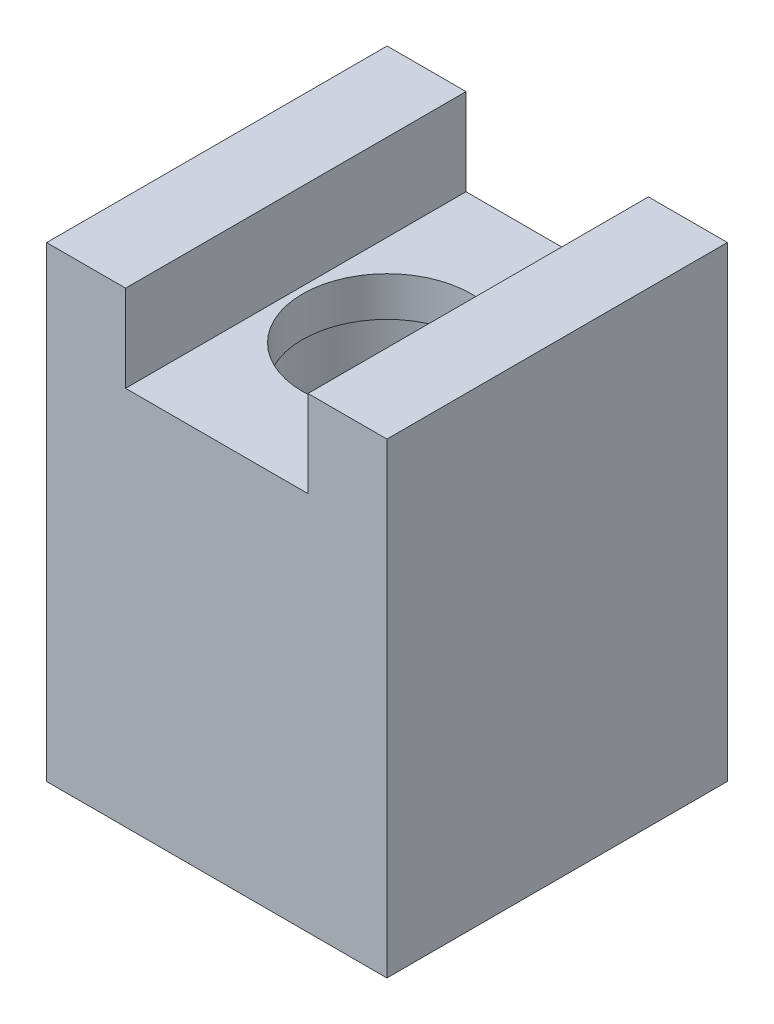
SolidWorks part; units mm, degrees
material "Alloy Steel (SS)"
ref_plane "Front Plane" through (0, 0, 0) normal (0, 0, 1) x (1, 0, 0)
ref_plane "Top Plane" through (0, 0, 0) normal (0, 1, 0) x (1, 0, 0)
ref_plane "Right Plane" through (0, 0, 0) normal (1, 0, 0) x (0, 0, -1)
sketch "Sketch1" plane through (0, 0, 0) normal (0, 1, 0) x (1, 0, 0)
  line L1 (-15.2171, -15.2248) -> (15.2171, -15.2248)
  line L2 (-15.2171, -15.2248) -> (-15.2171, 15.2248)
  line L3 (-15.2171, 15.2248) -> (15.2171, 15.2248)
  line L4 (15.2171, -15.2248) -> (15.2171, 15.2248)
  line L5 (-15.2171, -15.2248) -> (15.2171, 15.2248) construction
  line L6 (-15.2171, 15.2248) -> (15.2171, -15.2248) construction
  point P0 (0, 0)
  dimension "D1" = 30.4343
  dimension "D2" = 30.4495
extrude "Boss-Extrude1" add sketch "Sketch1" along normal blind 41.7424
sketch "Sketch4" plane through (0, 0, 0) normal (0, -1, 0) x (1, 0, 0)
  circle A0 centre (0, 0) radius 7.5565
  dimension "D1" = 15.113
extrude "Cut-Extrude3" cut sketch "Sketch4" against normal blind 36.5394
sketch "Sketch6" plane through (0, 41.7424, 0) normal (0, 1, 0) x (1, 0, 0)
  line L0 (15.2171, 15.2248) -> (-15.2171, 15.2248) construction
  line L1 (-8.1559, -15.2248) -> (8.1559, -15.2248)
  line L2 (-8.1559, -15.2248) -> (-8.1559, 15.2248)
  line L3 (-8.1559, 15.2248) -> (8.1559, 15.2248)
  line L4 (8.1559, -15.2248) -> (8.1559, 15.2248)
  line L5 (-8.1559, -15.2248) -> (8.1559, 15.2248) construction
  line L6 (-8.1559, 15.2248) -> (8.1559, -15.2248) construction
  line L7 (-15.2171, 15.2248) -> (-15.2171, -15.2248) construction
  point P0 (0, 0)
  dimension "D1" = 7.0612
extrude "Cut-Extrude5" cut sketch "Sketch6" against normal blind 7.7572
sketch "Sketch8" plane through (0, 0, 0) normal (0, -1, 0) x (1, 0, 0)
  circle A0 centre (0, 0) radius 11.2776
  dimension "D1" = 22.5552
extrude "Cut-Extrude6" cut sketch "Sketch8" against normal blind 30.4495
sketch "Sketch9" plane through (0, 0, 0) normal (0, -1, 0) x (1, 0, 0)
  line L0 (-15.2171, -15.2248) -> (-15.2171, 15.2248) construction
  line L1 (-15.2171, 15.2248) -> (15.2171, 15.2248) construction
  line L2 (0, -16.7472) -> (0, 16.7472) construction
  line L3 (16.7389, 0) -> (-16.7389, 0) construction
  circle A0 centre (-11.6205, 11.6281) radius 0.7937
  circle A1 centre (11.6205, 11.6281) radius 0.7937
  circle A2 centre (11.6205, -11.6281) radius 0.7937
  circle A3 centre (-11.6205, -11.6281) radius 0.7937
  dimension "D1" = 1.5875
  dimension "D2" = 3.5966
  dimension "D3" = 3.5966
hole_wizard "1/16 (0.0625) Diameter Hole1" positions "Sketch10" profile "Sketch11" hole size "1/16" standard "ANSI Inch"
sketch "Sketch10" plane through (0, 0, 0) normal (0, -1, 0) x (-1, 0, 0)
  point P0 (-11.6205, 11.6281)
  point P3 (11.6205, 11.6281)
  point P6 (11.6205, -11.6281)
  point P9 (-11.6205, -11.6281)
sketch "Sketch11" plane through (11.6205, 0, -11.6281) normal (1, 0, 0) x (0, 0, -1)
  line L0 (0, 0) -> (0, 13.1769)
  line L1 (0, 13.1769) -> (0.7937, 12.7)
  line L2 (0.7937, 12.7) -> (0.7937, 0.635)
  line L3 (0.7937, 0.635) -> (1.4287, 0)
  line L5 (1.4287, 0) -> (0, 0)
  line L6 (-0.7937, 0.635) -> (-1.4287, 0) construction
  line L10 (0, 13.1769) -> (-0.7937, 12.7) construction
  line L11 (0, -6.35) -> (0, 107.95) construction
  dimension "Hole Dia." = 1.5875
  dimension "Hole Depth" = 12.7
  dimension "Near C'Sink Dia." = 2.8575
  dimension "Near C'Sink Angle" = 90
  dimension "Drill Angle" = 118
